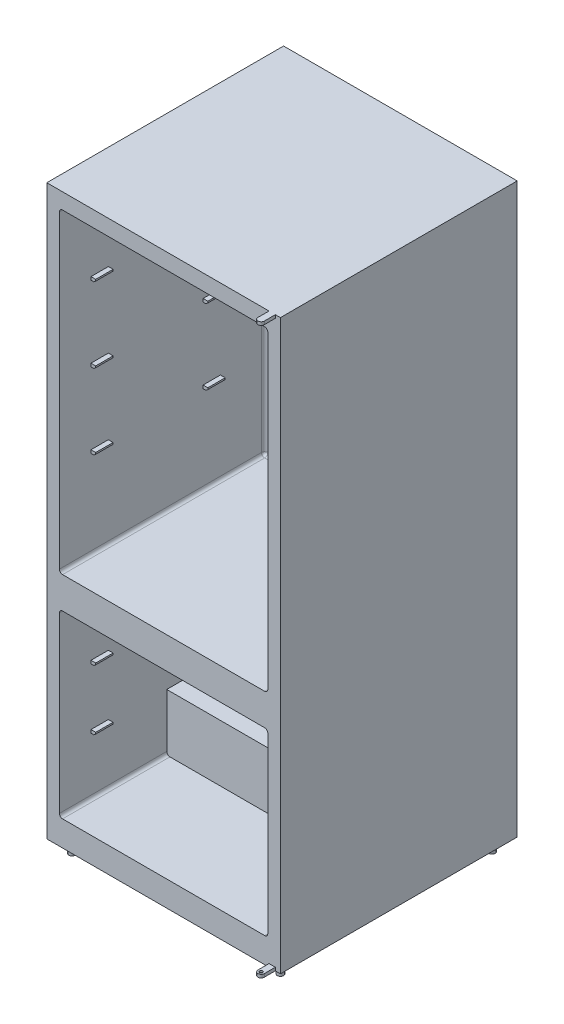
SolidWorks part; units mm, degrees
material "Aço cromo inoxidável"
ref_plane "Plano frontal" through (0, 0, 0) normal (0, 0, 1) x (1, 0, 0)
ref_plane "Plano superior" through (0, 0, 0) normal (0, 1, 0) x (1, 0, 0)
ref_plane "Plano direito" through (0, 0, 0) normal (1, 0, 0) x (0, 0, -1)
sketch "Esboço1" plane through (0, 0, 0) normal (0, 1, 0) x (1, 0, 0)
  line L0 (0, 0) -> (0, 750)
  line L1 (0, 750) -> (740, 750)
  line L2 (740, 750) -> (740, 0)
  line L3 (740, 0) -> (0, 0)
  dimension "D1" = 750
  dimension "D2" = 740
extrude "Ressalto-extrusão1" add sketch "Esboço1" along normal blind 1800
sketch "Esboço5" plane through (0, 0, 0) normal (0, 0, 1) x (1, 0, 0)
  line L0 (0, 1800) -> (740, 1800) construction
  line L1 (40, 1750) -> (700, 1750)
  line L2 (40, 1750) -> (40, 750)
  line L3 (40, 750) -> (700, 750)
  line L4 (700, 1750) -> (700, 750)
  line L5 (40, 650) -> (700, 650)
  line L6 (40, 650) -> (40, 80)
  line L7 (40, 80) -> (700, 80)
  line L8 (700, 650) -> (700, 80)
  line L10 (0, 1800) -> (0, 0) construction
  line L11 (0, 0) -> (740, 0) construction
  dimension "D1" = 50
  dimension "D3" = 40
  dimension "D4" = 80
  dimension "D5" = 100
  dimension "D6" = 1000
  dimension "D7" = 570
  dimension "D8" = 660
extrude "Corte-extrusão1" cut sketch "Esboço5" against normal blind 650
fillet "Filete1" radius 10 16 edges at (40, 365, -650) (370, 80, -650) (700, 365, -650) (370, 650, -650) (40, 80, -325) (700, 80, -325) (700, 650, -325) (40, 650, -325) (40, 1250, -650) (370, 750, -650) (700, 1250, -650) (370, 1750, -650) (700, 750, -325) (700, 1750, -325) (40, 1750, -325) (40, 750, -325)
sketch "Esboço7" plane through (0, 0, 0) normal (0, -1, 0) x (1, 0, 0)
  line L0 (40, -40) -> (700, -40) construction
  line L1 (700, -40) -> (700, -710) construction
  line L2 (700, -710) -> (40, -710) construction
  line L3 (40, -710) -> (40, -40) construction
  line L4 (0, -750) -> (0, 0) construction
  line L5 (740, 0) -> (740, -750) construction
  line L6 (0, 0) -> (740, 0) construction
  line L7 (740, -750) -> (0, -750) construction
  circle A0 centre (40, -40) radius 10
  circle A4 centre (700, -40) radius 10
  circle A5 centre (700, -710) radius 10
  circle A6 centre (40, -710) radius 10
  dimension "D5" = 20
  dimension "D1" = 40
  dimension "D2" = 40
  dimension "D3" = 40
  dimension "D4" = 40
extrude "Ressalto-extrusão3" add sketch "Esboço7" along normal blind 40
sketch "Esboço10" plane through (40, 0, 0) normal (1, 0, 0) x (0, 0, -1)
  line L0 (0, 1740) -> (0, 760) construction
  line L1 (100, 1512.5) -> (155, 1512.5)
  line L2 (100, 1512.5) -> (100, 1502.5)
  line L3 (100, 1502.5) -> (155, 1502.5)
  line L4 (155, 1512.5) -> (155, 1502.5)
  line L7 (0, 1750) -> (640, 1750) construction
  line L8 (455, 1512.5) -> (510, 1512.5)
  line L9 (455, 1502.5) -> (510, 1502.5)
  line L10 (510, 1512.5) -> (510, 1502.5)
  line L11 (455, 1512.5) -> (455, 1502.5)
  line L12 (455, 1275) -> (510, 1275)
  line L13 (455, 1265) -> (510, 1265)
  line L14 (510, 1275) -> (510, 1265)
  line L15 (455, 1275) -> (455, 1265)
  line L16 (455, 1037.5) -> (510, 1037.5)
  line L17 (455, 1027.5) -> (510, 1027.5)
  line L18 (510, 1037.5) -> (510, 1027.5)
  line L19 (455, 1037.5) -> (455, 1027.5)
  line L20 (100, 1275) -> (155, 1275)
  line L21 (100, 1265) -> (155, 1265)
  line L22 (155, 1275) -> (155, 1265)
  line L23 (100, 1275) -> (100, 1265)
  line L24 (100, 1037.5) -> (155, 1037.5)
  line L25 (100, 1027.5) -> (155, 1027.5)
  line L26 (155, 1037.5) -> (155, 1027.5)
  line L27 (100, 1037.5) -> (100, 1027.5)
  point P9 (455, 1507.5)
  dimension "D1" = 55
  dimension "D2" = 100
  dimension "D3" = 10
  dimension "D4" = 237.5
  dimension "D5" = 3
  dimension "D7" = 300
  dimension "D8" = 227.5
  dimension "D9" = 100
  dimension "D6" = 2
extrude "Ressalto-extrusão4" add sketch "Esboço10" along normal blind 15
ref_plane "Plano1" through (370, 0, 0) normal (1, 0, 0) x (0, 0, -1)
mirror "Espelhar4" about plane through (370, 0, 0) normal (1, 0, 0) of "Ressalto-extrusão4"
sketch "Esboço14" plane through (40, 0, 0) normal (1, 0, 0) x (0, 0, -1)
  line L0 (100, 460) -> (155, 460)
  line L1 (155, 460) -> (155, 450)
  line L2 (155, 450) -> (100, 450)
  line L3 (100, 450) -> (100, 460)
  line L4 (0, 650) -> (640, 650) construction
  line L5 (0, 640) -> (0, 90) construction
  line L6 (455, 460) -> (510, 460)
  line L7 (455, 450) -> (455, 460)
  line L8 (510, 450) -> (455, 450)
  line L9 (510, 460) -> (510, 450)
  line L10 (455, 270) -> (510, 270)
  line L11 (455, 260) -> (455, 270)
  line L12 (510, 260) -> (455, 260)
  line L13 (510, 270) -> (510, 260)
  line L14 (100, 270) -> (155, 270)
  line L15 (100, 260) -> (100, 270)
  line L16 (155, 260) -> (100, 260)
  line L17 (155, 270) -> (155, 260)
  line L18 (100, 460) -> (455, 460) construction
  point P8 (127.5, 450)
  point P9 (155, 455)
  dimension "D1" = 190
  dimension "D2" = 10
  dimension "D3" = 100
  dimension "D4" = 55
  dimension "D6" = 300
  dimension "D8" = 190
  dimension "D9" = 100
  dimension "D7" = 2
  dimension "D5" = 2
extrude "Ressalto-extrusão5" add sketch "Esboço14" along normal blind 15
mirror "Espelhar5" about plane through (370, 0, 0) normal (1, 0, 0) of "Ressalto-extrusão5"
chamfer "Chanfro1" distance 5 angle 50 20 edges at (685, 260, -482.5) (685, 260, -127.5) (685, 450, -127.5) (685, 450, -482.5) (685, 1027.5, -482.5) (685, 1027.5, -127.5) (685, 1265, -127.5) (685, 1265, -482.5) (685, 1502.5, -127.5) (685, 1502.5, -482.5) (55, 260, -127.5) (55, 450, -127.5) (55, 260, -482.5) (55, 450, -482.5) (55, 1027.5, -127.5) (55, 1027.5, -482.5) (55, 1265, -127.5) (55, 1265, -482.5) (55, 1502.5, -127.5) (55, 1502.5, -482.5)
sketch "Esboço17" plane through (0, 1800, 0) normal (0, 1, 0) x (1, 0, 0)
  line L0 (0, 0) -> (740, 0) construction
  line L1 (703.893, 0) -> (723.893, 0)
  line L2 (703.893, 0) -> (703.893, -35)
  line L4 (723.893, 0) -> (723.893, -35)
  arc A0 (703.893, -35) -> (723.893, -35) centre (713.893, -35) ccw
  dimension "D2" = 10
  dimension "D1" = 35
  dimension "D3" = 26.107
extrude "Ressalto-extrusão6" add sketch "Esboço17" against normal blind 10
sketch "Esboço18" plane through (0, 1790, 0) normal (0, -1, 0) x (1, 0, 0)
  circle A0 centre (713.893, 35) radius 5
  dimension "D1" = 10
extrude "Corte-extrusão2" cut sketch "Esboço18" against normal blind 5
ref_plane "Plano3" through (0, 900, 0) normal (0, 1, 0) x (1, 0, 0)
mirror "Espelhar6" about plane through (0, 900, 0) normal (0, 1, 0) of "Corte-extrusão2", "Ressalto-extrusão6"
sketch "Esboço19" plane through (0, 0, -750) normal (0, 0, -1) x (-1, 0, 0)
  line L1 (-730, 250) -> (-10, 250)
  line L3 (-730, 10) -> (-10, 10)
  line L6 (-740, 0) -> (0, 0) construction
  line L7 (-690, 260) -> (-700, 260) construction
  line L8 (-10, 250) -> (-10, 10)
  line L9 (-730, 10) -> (-730, 250)
  line L10 (0, 1800) -> (0, 0) construction
  line L11 (-740, 1800) -> (-740, 0) construction
  dimension "D1" = 10
  dimension "D2" = 10
  dimension "D3" = 10
  dimension "D4" = 10
extrude "Corte-extrusão5" cut sketch "Esboço19" against normal blind 400
sketch "Esboço21" plane through (700, 0, 0) normal (-1, 0, 0) x (0, 0, 1)
  line L0 (-640, 640) -> (-640, 250) construction
  line L1 (-640, 250) -> (-350, 250)
  line L4 (-350, 250) -> (-350, 0)
  line L5 (-640, 260) -> (-340, 260)
  line L6 (-640, 260) -> (-640, 250)
  line L7 (-350, 0) -> (-340, 0)
  line L8 (-340, 260) -> (-340, 0)
  line L10 (-750, 0) -> (0, 0) construction
  line L12 (-750, 1800) -> (-750, 0) construction
  dimension "D1" = 10
  dimension "D2" = 10
  dimension "D3" = 400
extrude "Ressalto-extrusão8" add sketch "Esboço21" along normal up to next
